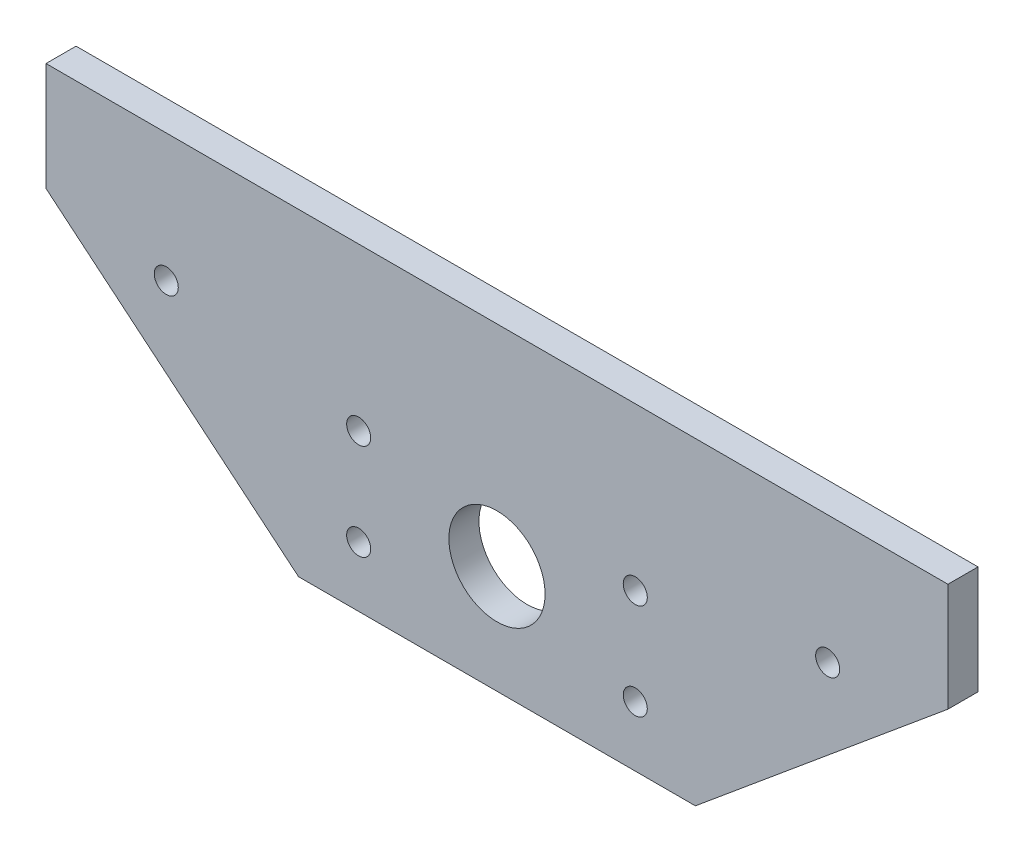
SolidWorks part; units mm, degrees
material "아크릴(내충격성)"
ref_plane "정면" through (0, 0, 0) normal (0, 0, 1) x (1, 0, 0)
ref_plane "윗면" through (0, 0, 0) normal (0, 1, 0) x (1, 0, 0)
ref_plane "우측면" through (0, 0, 0) normal (1, 0, 0) x (0, 0, -1)
sketch "스케치1" plane through (0, 0, 0) normal (0, 0, 1) x (1, 0, 0)
  line L1 (-75, 34.9192) -> (75, 34.9192)
  line L2 (-75, 34.9192) -> (-75, -35.0808)
  line L3 (-75, -35.0808) -> (75, -35.0808)
  line L4 (75, 34.9192) -> (75, -35.0808)
  line L5 (-75, 34.9192) -> (75, -35.0808) construction
  line L6 (-75, -35.0808) -> (75, 34.9192) construction
  dimension "D1" = 150
  dimension "D2" = 70
extrude "보스-돌출1" add sketch "스케치1" along normal blind 5
sketch "스케치2" plane through (0, 0, 5) normal (0, 0, 1) x (1, 0, 0)
  circle A0 centre (0, 0) radius 8
extrude "컷-돌출1" cut sketch "스케치2" against normal through all
sketch "스케치3" plane through (0, 0, 5) normal (0, 0, 1) x (1, 0, 0)
  line L0 (-56.0789, 0) -> (55.5902, 0) construction
  line L1 (0, 49.5425) -> (0, -49.6646) construction
  line L2 (-56.0789, -15) -> (55.5902, -15)
  line L3 (-56.0789, 15) -> (55.5902, 15)
  line L4 (-30, 49.5425) -> (-30, -49.6646)
  line L5 (30, 49.5425) -> (30, -49.6646)
  circle A0 centre (-23, 8) radius 2
  circle A1 centre (-23, -8) radius 2
  circle A2 centre (23, -8) radius 2
  circle A3 centre (23, 8) radius 2
  dimension "D5" = 4
  dimension "D6" = 7
  dimension "D7" = 7
  dimension "D1" = 15
  dimension "D2" = 15
  dimension "D3" = 30
  dimension "D4" = 30
extrude "컷-돌출2" cut sketch "스케치3" against normal through all contours A0 | A1 | A2 | A3
sketch "스케치4" plane through (0, 0, 5) normal (0, 0, 1) x (1, 0, 0)
  line L0 (0, 49.097) -> (0, -61.2799) construction
  line L1 (-75, 34.9192) -> (-75, -35.0808) construction
  line L2 (-75, -35.0808) -> (75, -35.0808) construction
  circle A0 centre (-55, 13.649) radius 2
  circle A1 centre (-65, -25.0808) radius 2
  circle A2 centre (65, -25.0808) radius 2
  circle A3 centre (55, 13.649) radius 2
  dimension "D1" = 4
  dimension "D2" = 4
  dimension "D3" = 10
  dimension "D4" = 10
  dimension "D5" = 20
  dimension "D6" = 40
extrude "컷-돌출3" cut sketch "스케치4" against normal through all
sketch "스케치5" plane through (0, 0, 5) normal (0, 0, 1) x (1, 0, 0)
  line L0 (-56.981, 13.9238) -> (56.981, 13.9238) construction
  line L1 (-65, -27.0808) -> (65, -27.0808) construction
  line L2 (-45, 25.7976) -> (-45, -31.7862) construction
  line L3 (-33, 24.5979) -> (-33, -29.3868) construction
  line L4 (33, 24.5979) -> (33, -29.3868) construction
  line L5 (45, 24.5979) -> (45, -30.7579) construction
  line L6 (-75, 16.9192) -> (-33, -18)
  line L16 (-75, 34.9192) -> (-75, -35.0808) construction
  line L18 (75, -35.0808) -> (75, 34.9192) construction
  line L19 (75, 16.9192) -> (75, -35.0808)
  line L20 (75, -35.0808) -> (-75, -35.0808)
  line L21 (-75, -35.0808) -> (-75, -27.0808)
  line L22 (75, 16.9192) -> (33, -18)
  line L23 (-75, 16.9192) -> (-75, -27.0808)
  line L25 (-33, -18) -> (33, -18)
  line L26 (-23, 8) -> (-23, 13.9238) construction
  line L27 (-56.981, 13.9238) -> (-23, 13.9238) construction
  circle A0 centre (-55, 13.649) radius 2 construction
  circle A1 centre (55, 13.649) radius 2 construction
  circle A2 centre (-23, -8) radius 2 construction
  circle A4 centre (65, -25.0808) radius 2 construction
  circle A5 centre (-23, 8) radius 2 construction
  circle A6 centre (23, 8) radius 2 construction
  point P9 (-65, -27.0808)
  dimension "D1" = 10
  dimension "D3" = 10
  dimension "D5" = 10
  dimension "D2" = 10
  dimension "D4" = 10
extrude "컷-돌출4" cut sketch "스케치5" against normal through all
